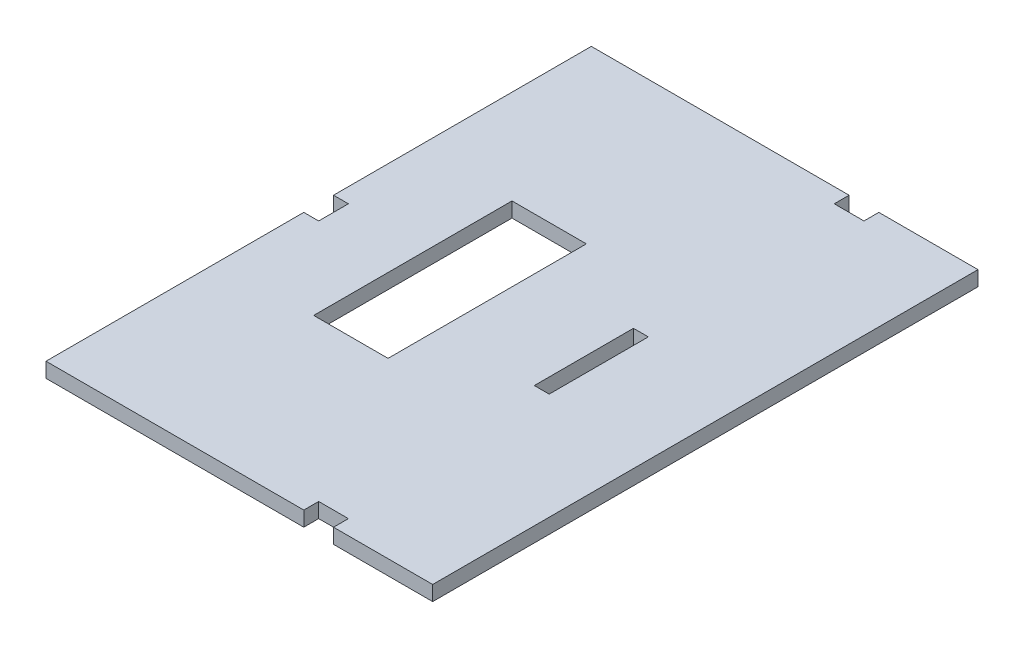
SolidWorks part; units mm, degrees
ref_plane "Спереди" through (0, 0, 0) normal (0, 0, 1) x (1, 0, 0)
ref_plane "Сверху" through (0, 0, 0) normal (0, 1, 0) x (1, 0, 0)
ref_plane "Справа" through (0, 0, 0) normal (1, 0, 0) x (0, 0, -1)
other "Configuration Table"
sketch "Эскиз4" plane through (0, 0, 0) normal (0, 1, 0) x (1, 0, 0)
  line L0 (78, 110) -> (78, 0)
  line L1 (0, 0) -> (52, 0)
  line L2 (0, 0) -> (0, 52)
  line L3 (0, 110) -> (52, 110)
  line L5 (58, 0) -> (78, 0)
  line L6 (55, 107) -> (55, 3) construction
  line L7 (52, 107) -> (55, 107)
  line L8 (55, 107) -> (58, 107)
  line L9 (52, 107) -> (52, 110)
  line L10 (58, 107) -> (58, 110)
  line L11 (58, 3) -> (58, 0)
  line L12 (55, 3) -> (58, 3)
  line L13 (55, 3) -> (52, 3)
  line L14 (52, 3) -> (52, 0)
  line L15 (3, 55) -> (3, 58)
  line L16 (3, 55) -> (3, 52)
  line L17 (3, 58) -> (0, 58)
  line L18 (3, 52) -> (0, 52)
  line L19 (0, 58) -> (0, 110)
  line L20 (58, 110) -> (78, 110)
  dimension "D1" = 110
  dimension "D2" = 55
  dimension "D3" = 3
  dimension "D4" = 3
  dimension "D5" = 3
  dimension "D6" = 3
  dimension "D7" = 3
  dimension "D8" = 3
  dimension "D9" = 3
  dimension "D10" = 20
extrude "Бобышка-Вытянуть3" add sketch "Эскиз4" along normal blind 3
sketch "Sketch1" plane through (0, 3, 0) normal (0, 1, 0) x (1, 0, 0)
  line L0 (3, 52) -> (3, 58) construction
  line L13 (3, 55) -> (107, 55) construction
  line L15 (55, 107) -> (55, 3) construction
  line L16 (52, 107) -> (58, 107) construction
  line L17 (58, 3) -> (52, 3) construction
  line L19 (19, 75) -> (34, 75)
  line L20 (19, 75) -> (19, 35)
  line L21 (19, 35) -> (34, 35)
  line L22 (34, 75) -> (34, 35)
  line L23 (53.5, 65) -> (56.5, 65)
  line L24 (53.5, 65) -> (53.5, 45)
  line L25 (53.5, 45) -> (56.5, 45)
  line L26 (56.5, 65) -> (56.5, 45)
  point P8 (56.5, 65)
  point P9 (107, 55)
  dimension "D1" = 3
  dimension "D2" = 20
  dimension "D3" = 16
  dimension "D4" = 15
  dimension "D5" = 40
extrude "Cut-Extrude1" cut sketch "Sketch1" against normal blind 10
